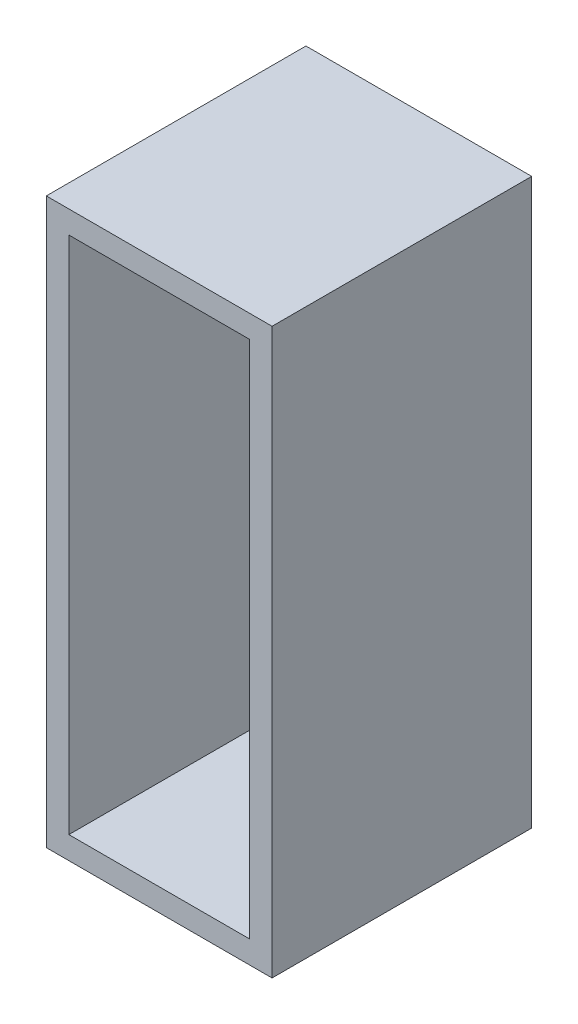
SolidWorks part; units mm, degrees
ref_plane "Front Plane" through (0, 0, 0) normal (0, 0, 1) x (1, 0, 0)
ref_plane "Top Plane" through (0, 0, 0) normal (0, 1, 0) x (1, 0, 0)
ref_plane "Right Plane" through (0, 0, 0) normal (1, 0, 0) x (0, 0, -1)
sketch "Sketch2" plane through (0, 0, 0) normal (0, 0, 1) x (1, 0, 0)
  line L0 (0, 0) -> (0, -50)
  line L1 (0, -50) -> (-20, -50)
  line L2 (-20, -50) -> (-20, 0)
  line L3 (-20, 0) -> (0, 0)
extrude "Boss-Extrude1" add sketch "Sketch2" along normal blind 23
sketch "Sketch3" plane through (0, 0, 23) normal (0, 0, 1) x (1, 0, 0)
  line L0 (-18, -2) -> (-2, -2)
  line L1 (-18, -2) -> (-18, -48)
  line L2 (-18, -48) -> (-2, -48)
  line L3 (-2, -2) -> (-2, -48)
  line L4 (-20, 0) -> (-20, -50) construction
  line L5 (0, -50) -> (0, 0) construction
  line L6 (0, 0) -> (-20, 0) construction
  line L7 (-20, -50) -> (0, -50) construction
  dimension "D1" = 2
  dimension "D2" = 2
  dimension "D3" = 2
  dimension "D4" = 2
extrude "Cut-Extrude1" cut sketch "Sketch3" against normal blind 21
